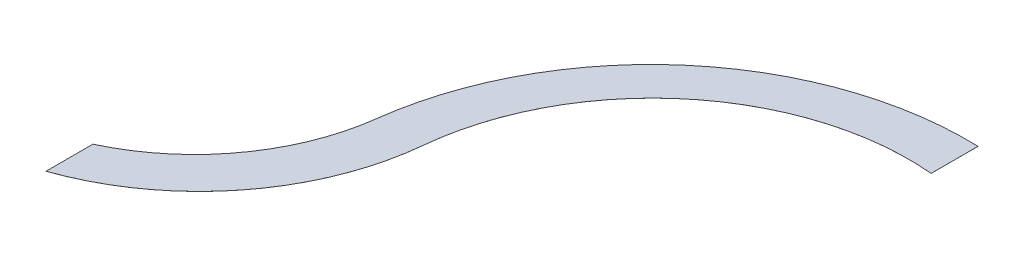
SolidWorks part; units mm, degrees
ref_plane "Plano frontal" through (0, 0, 0) normal (0, 0, 1) x (1, 0, 0)
ref_plane "Plano superior" through (0, 0, 0) normal (0, 1, 0) x (1, 0, 0)
ref_plane "Plano direito" through (0, 0, 0) normal (1, 0, 0) x (0, 0, -1)
sketch "Esboço1" plane through (0, 0, 0) normal (0, 1, 0) x (1, 0, 0)
  line L0 (-1093, 595.536) -> (-1073, 595.536)
  line L1 (0, 0) -> (18.9344, 0)
  line L2 (0, 0) -> (0, 766.8662)
  line L3 (0, 766.8662) -> (18.9344, 766.8662)
  line L4 (18.9344, 0) -> (18.9344, 766.8662)
  line L5 (-381.6968, 766.8662) -> (-362.7624, 766.8662)
  line L6 (-381.6968, 766.8662) -> (-381.6968, 345.536)
  line L7 (-381.6968, 345.536) -> (-362.7624, 345.536)
  line L8 (-362.7624, 766.8662) -> (-362.7624, 345.536)
  line L9 (-858.9344, 645.536) -> (-840, 645.536)
  line L10 (-858.9344, 645.536) -> (-858.9344, 345.536)
  line L11 (-858.9344, 345.536) -> (-840, 345.536)
  line L12 (-840, 645.536) -> (-840, 345.536)
  line L13 (-853.5858, 925.2213) -> (-1253.5858, 925.2213)
  line L14 (-853.5858, 925.2213) -> (-853.5858, 945.2213)
  line L15 (-853.5858, 945.2213) -> (-1253.5858, 945.2213)
  line L16 (-1253.5858, 925.2213) -> (-1253.5858, 945.2213)
  line L17 (-1093, 595.536) -> (-1093, 195.536)
  line L18 (-1093, 195.536) -> (-1073, 195.536)
  line L19 (-1073, 595.536) -> (-1073, 195.536)
  line L21 (-858.9344, 427.7897) -> (-1250.0103, 427.7897)
  line L23 (-858.9344, 407.7897) -> (-1250.0103, 407.7897)
  line L24 (-1250.0103, 427.7897) -> (-1250.0103, 407.7897)
  line L33 (-1439.6613, 239.7512) -> (-1560.0448, 239.7512)
  line L34 (-1439.6613, 239.7512) -> (-1439.6613, 219.7512)
  line L35 (-1439.6613, 219.7512) -> (-1560.0448, 219.7512)
  line L36 (-1560.0448, 239.7512) -> (-1560.0448, 219.7512)
  line L37 (-1627.2015, 576.144) -> (-1607.2015, 576.144)
  line L38 (-1627.2015, 576.144) -> (-1627.2015, 317.0654)
  line L39 (-1627.2015, 317.0654) -> (-1607.2015, 317.0654)
  line L40 (-1607.2015, 576.144) -> (-1607.2015, 317.0654)
  line L41 (-1627.2015, 769.6927) -> (-1607.2015, 769.6927)
  line L42 (-1627.2015, 769.6927) -> (-1627.2015, 1019.6927)
  line L43 (-1627.2015, 1019.6927) -> (-1607.2015, 1019.6927)
  line L44 (-1607.2015, 769.6927) -> (-1607.2015, 1019.6927)
  line L45 (670.3987, 1026.1809) -> (670.3987, 1006.1809)
  line L46 (480.7477, 838.1424) -> (480.7477, 818.1424)
  arc A6 (-381.6968, 766.8662) -> (18.9344, 766.8662) centre (-181.3812, 766.8662) cw
  arc A7 (-362.7624, 766.8662) -> (0, 766.8662) centre (-181.3812, 766.8662) cw
  arc A8 (-362.7624, 345.536) -> (-858.9344, 345.536) centre (-610.8484, 345.536) cw
  arc A9 (-381.6968, 345.536) -> (-840, 345.536) centre (-610.8484, 345.536) cw
  arc A10 (-840, 645.536) -> (-803.6955, 702.0415) centre (-777.8744, 645.536) cw
  arc A11 (-803.6955, 702.0415) -> (-853.5858, 945.2213) centre (-856.6336, 817.8884) ccw
  arc A12 (-858.9344, 645.536) -> (-814.4955, 717.9247) centre (-777.7563, 645.536) cw
  arc A13 (-814.4955, 717.9247) -> (-853.5858, 925.2213) centre (-864.2122, 815.8835) ccw
  arc A14 (-1093, 595.536) -> (-1188.5366, 677.9223) centre (-1176.2913, 595.536) ccw
  arc A15 (-1188.5366, 677.9223) -> (-1354.3411, 742.8189) centre (-1214.8489, 854.9525) cw
  arc A16 (-1354.3411, 742.8189) -> (-1253.5858, 945.2213) centre (-1257.3278, 820.805) cw
  arc A17 (-1073, 595.536) -> (-1188.5366, 698.0004) centre (-1176.2038, 595.536) ccw
  arc A18 (-1188.5366, 698.0004) -> (-1341.8208, 766.8662) centre (-1207.9995, 859.705) cw
  arc A19 (-1341.8208, 766.8662) -> (-1253.5858, 925.2213) centre (-1258.876, 824.4093) cw
  arc A22 (-1368.7558, 309.7722) -> (-1439.6613, 219.7512) centre (-1474.849, 320.402) cw
  arc A23 (-1388.5562, 309.7722) -> (-1439.6613, 239.7512) centre (-1477.6183, 321.1143) cw
  arc A24 (-1388.5562, 309.7722) -> (-1250.0103, 427.7897) centre (-1254.4723, 292.6965) cw
  arc A25 (-1607.2015, 317.0654) -> (-1560.0448, 239.7512) centre (-1520.2441, 317.0654) ccw
  arc A26 (-1627.2015, 317.0654) -> (-1560.0448, 219.7512) centre (-1523.1159, 317.0654) ccw
  arc A27 (-1368.7558, 309.7722) -> (-1250.0103, 407.7897) centre (-1259.9289, 298.8686) cw
  arc A28 (551.6532, 908.1634) -> (480.7477, 818.1424) centre (445.56, 918.7932) cw
  arc A29 (531.8527, 908.1634) -> (480.7477, 838.1424) centre (442.7907, 919.5055) cw
  arc A30 (531.8527, 908.1634) -> (670.3987, 1026.1809) centre (665.9366, 891.0877) cw
  arc A31 (551.6532, 908.1634) -> (670.3987, 1006.1809) centre (660.4801, 897.2598) cw
extrude "Ressalto-extrusão14" add sketch "Esboço1" along normal blind 0.01 contours A31 L45 A30 A29 L46 A28
